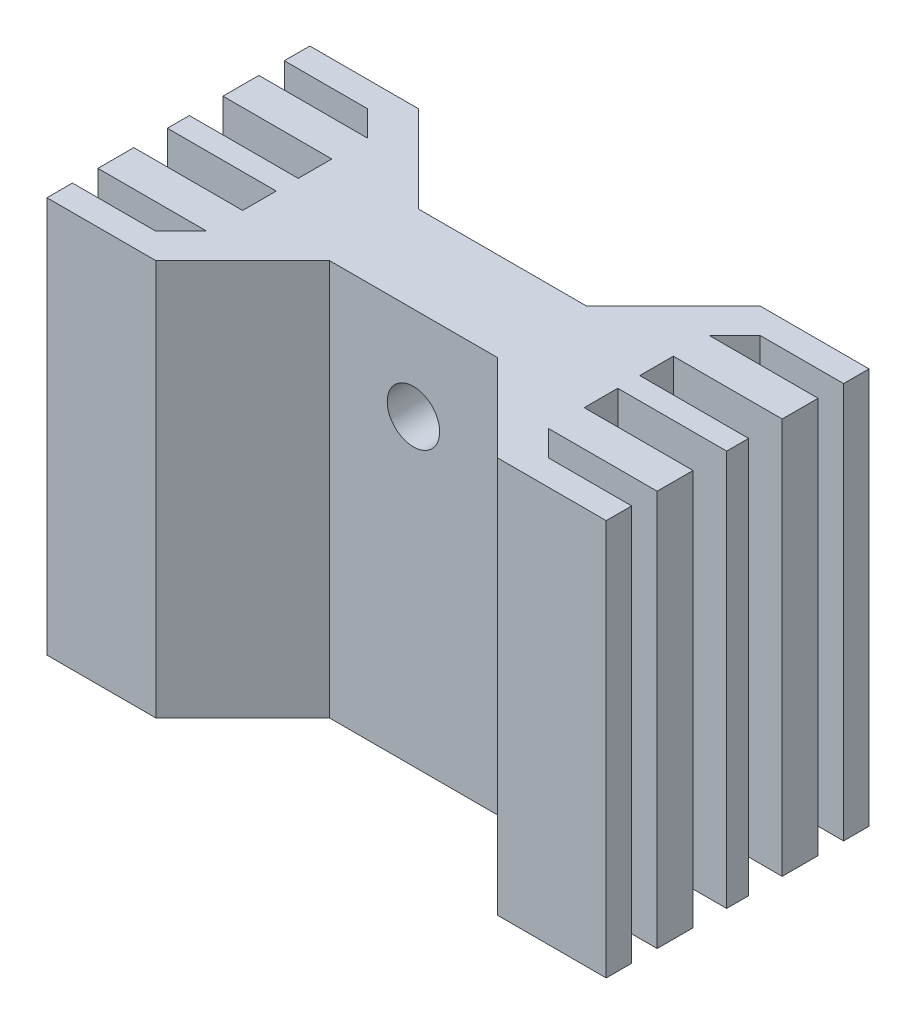
SolidWorks part; units mm, degrees
ref_plane "Front Plane" through (0, 0, 0) normal (0, 0, 1) x (1, 0, 0)
ref_plane "Top Plane" through (0, 0, 0) normal (0, 1, 0) x (1, 0, 0)
ref_plane "Right Plane" through (0, 0, 0) normal (1, 0, 0) x (0, 0, -1)
sketch "Sketch1" plane through (0, 0, 0) normal (0, 1, 0) x (1, 0, 0)
  line L0 (-59.338, 25.1675) -> (-40.1043, 25.1675)
  line L1 (-40.1043, 25.1675) -> (-24.7583, 9.8215)
  line L2 (-24.7583, 9.8215) -> (4.9107, 9.8215)
  line L3 (-59.338, 25.1675) -> (-59.338, 20.666)
  line L4 (-59.338, 20.666) -> (-44.6058, 20.666)
  line L5 (-44.6058, 20.666) -> (-40.1043, 16.1645)
  line L6 (-40.1043, 16.1645) -> (-59.338, 16.1645)
  line L7 (-59.338, 16.1645) -> (-59.338, 9.8215)
  line L8 (-59.338, 9.8215) -> (-40.1043, 9.8215)
  line L9 (-40.1043, 9.8215) -> (-40.1043, 3.8877)
  line L10 (-40.1043, 3.8877) -> (-59.338, 3.8877)
  line L11 (-59.338, 3.8877) -> (-59.338, 0)
  line L12 (-24.7583, -5.9338) -> (4.9107, -5.9338)
  line L13 (-40.1043, 0) -> (-59.338, 0)
  line L20 (-40.1043, -5.9338) -> (-40.1043, 0)
  line L21 (-59.338, -5.9338) -> (-40.1043, -5.9338)
  line L22 (-59.338, -12.2768) -> (-59.338, -5.9338)
  line L23 (-40.1043, -12.2768) -> (-59.338, -12.2768)
  line L24 (-44.6058, -16.7783) -> (-40.1043, -12.2768)
  line L25 (-59.338, -16.7783) -> (-44.6058, -16.7783)
  line L26 (-59.338, -21.2798) -> (-59.338, -16.7783)
  line L27 (-40.1043, -21.2798) -> (-24.7583, -5.9338)
  line L28 (-59.338, -21.2798) -> (-40.1043, -21.2798)
  line L29 (39.4905, -21.2798) -> (20.2568, -21.2798)
  line L30 (20.2568, -21.2798) -> (4.9107, -5.9338)
  line L31 (39.4905, -21.2798) -> (39.4905, -16.7783)
  line L32 (39.4905, -16.7783) -> (24.7583, -16.7783)
  line L33 (24.7583, -16.7783) -> (20.2568, -12.2768)
  line L34 (20.2568, -12.2768) -> (39.4905, -12.2768)
  line L35 (39.4905, -12.2768) -> (39.4905, -5.9338)
  line L36 (39.4905, -5.9338) -> (20.2568, -5.9338)
  line L37 (20.2568, -5.9338) -> (20.2568, 0)
  line L38 (20.2568, 0) -> (39.4905, 0)
  line L39 (39.4905, 3.8877) -> (39.4905, 0)
  line L40 (20.2568, 3.8877) -> (39.4905, 3.8877)
  line L41 (20.2568, 9.8215) -> (20.2568, 3.8877)
  line L42 (39.4905, 9.8215) -> (20.2568, 9.8215)
  line L43 (39.4905, 16.1645) -> (39.4905, 9.8215)
  line L44 (20.2568, 16.1645) -> (39.4905, 16.1645)
  line L45 (24.7583, 20.666) -> (20.2568, 16.1645)
  line L46 (39.4905, 20.666) -> (24.7583, 20.666)
  line L47 (39.4905, 25.1675) -> (39.4905, 20.666)
  line L48 (20.2568, 25.1675) -> (4.9107, 9.8215)
  line L49 (39.4905, 25.1675) -> (20.2568, 25.1675)
extrude "Boss-Extrude1" add sketch "Sketch1" along normal blind 70 contours L12 L30 L29 L31 L32 L33 L34 L35 L36 L37 L38 L39 L40 L41 L42 L43 L44 L45 L46 L47 L49 L48 L2 L1 L0 L3 L4 L5 L6 L7 L8 L9 L10 L11 L13 L20 L21 L22 L23 L24 L25 L26 L28 L27
sketch "Sketch3" plane through (0, 0, -9.8215) normal (0, 0, -1) x (-1, 0, 0)
  line L0 (9.9238, 70) -> (9.9238, 0) construction
  line L1 (24.7583, 70) -> (-4.9107, 70) construction
  line L2 (24.7583, 0) -> (-4.9107, 0) construction
  circle A0 centre (9.9238, 53.535) radius 4.6306
extrude "Cut-Extrude1" cut sketch "Sketch3" against normal through all
